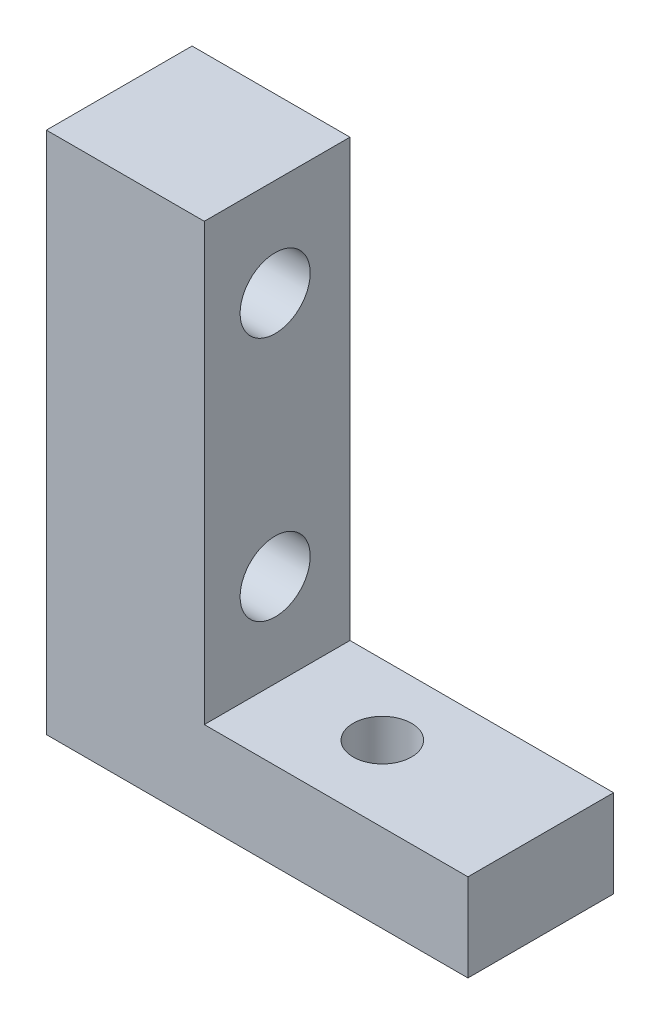
SolidWorks part; units mm, degrees
ref_plane "Front Plane" through (0, 0, 0) normal (0, 0, 1) x (1, 0, 0)
ref_plane "Top Plane" through (0, 0, 0) normal (0, 1, 0) x (1, 0, 0)
ref_plane "Right Plane" through (0, 0, 0) normal (1, 0, 0) x (0, 0, -1)
sketch "Sketch1" plane through (0, 0, 0) normal (0, 1, 0) x (1, 0, 0)
  line L1 (0, 0) -> (18.3257, 0)
  line L2 (0, 0) -> (0, 6.3327)
  line L3 (0, 6.3327) -> (18.3257, 6.3327)
  line L4 (18.3257, 0) -> (18.3257, 6.3327)
  circle A0 centre (11.3204, 3.2844) radius 1.27
  dimension "D1" = 2.54
extrude "Boss-Extrude1" add sketch "Sketch1" along normal blind 3.81
sketch "Sketch2" plane through (0, 0, 0) normal (-1, 0, 0) x (0, 0, 1)
  line L0 (-6.3327, 0) -> (0, 0) construction
  line L1 (0, 3.81) -> (-6.3327, 3.81)
  line L2 (0, 3.81) -> (0, 22.7594)
  line L3 (0, 22.7594) -> (-6.3327, 22.7594)
  line L4 (-6.3327, 3.81) -> (-6.3327, 22.7594)
  line L5 (-3.0802, 23.9901) -> (-3.0802, 2.54) construction
  circle A0 centre (-3.0802, 18.5144) radius 1.524
  circle A1 centre (-3.0802, 7.8464) radius 1.524
  dimension "D1" = 3.048
  dimension "D2" = 4.245
  dimension "D3" = 10.668
extrude "Boss-Extrude2" add sketch "Sketch2" against normal blind 6.8647
